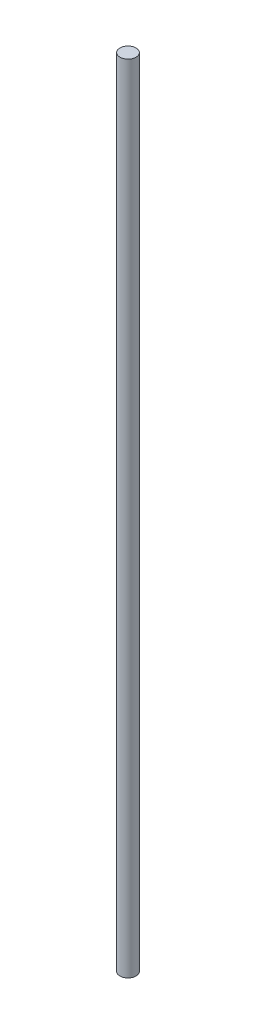
SolidWorks part; units mm, degrees
material "5052-H34"
ref_plane "Front Plane" through (0, 0, 0) normal (0, 0, 1) x (1, 0, 0)
ref_plane "Top Plane" through (0, 0, 0) normal (0, 1, 0) x (1, 0, 0)
ref_plane "Right Plane" through (0, 0, 0) normal (1, 0, 0) x (0, 0, -1)
sketch "Sketch1" plane through (0, 0, 0) normal (0, 1, 0) x (1, 0, 0)
  circle A0 centre (0, 0) radius 1
  dimension "D1" = 2
extrude "Boss-Extrude1" add sketch "Sketch1" along normal mid plane 99
